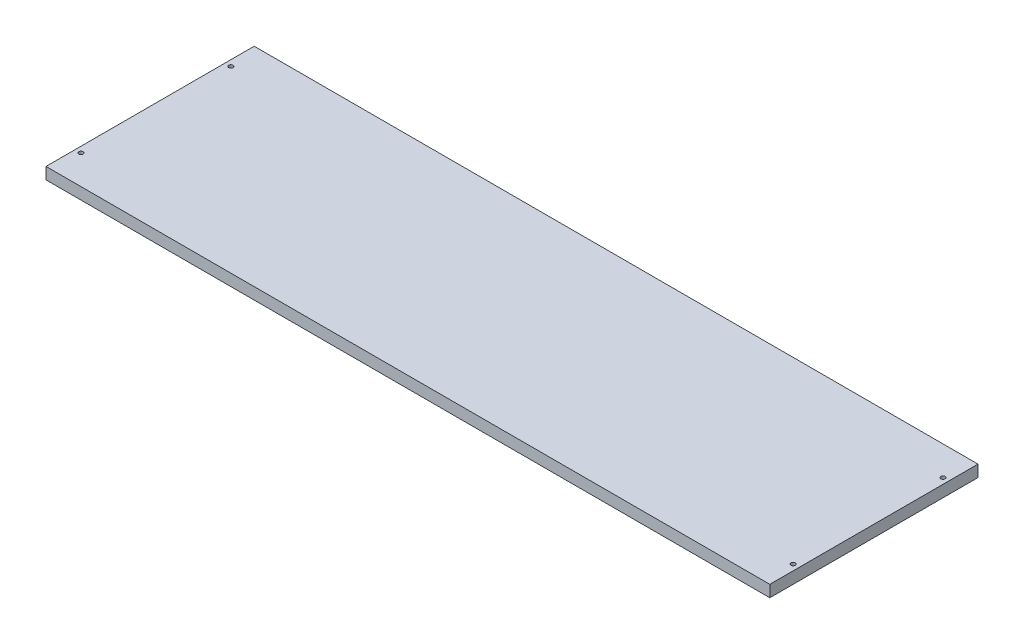
SolidWorks part; units mm, degrees
material "Дуб"
ref_plane "Front Plane" through (0, 0, 0) normal (0, 0, 1) x (1, 0, 0)
ref_plane "Top Plane" through (0, 0, 0) normal (0, 1, 0) x (1, 0, 0)
ref_plane "Right Plane" through (0, 0, 0) normal (1, 0, 0) x (0, 0, -1)
sketch "Эскиз1" plane through (0, 0, 0) normal (0, 1, 0) x (1, 0, 0)
  line L1 (-372, 107) -> (0, 107)
  line L2 (-372, 107) -> (-372, 0)
  line L3 (-372, 0) -> (0, 0)
  line L4 (0, 107) -> (0, 0)
  circle A0 centre (-369, 92) radius 1.1
  circle A1 centre (-369, 15) radius 1.1
  circle A2 centre (-3, 92) radius 1.1
  circle A3 centre (-3, 15) radius 1.1
  dimension "D3" = 2.2
  dimension "D4" = 3
  dimension "D5" = 3
  dimension "D6" = 15
  dimension "D7" = 15
  dimension "D1" = 107
  dimension "D2" = 372
extrude "Бобышка-Вытянуть1" add sketch "Эскиз1" along normal blind 6
